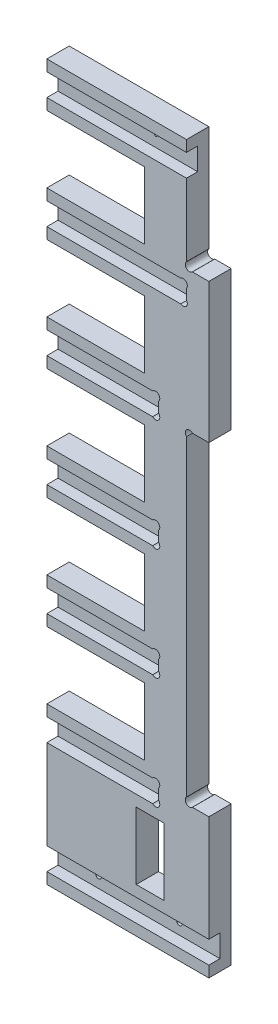
SolidWorks part; units mm, degrees
ref_plane "Plan de face" through (0, 0, 0) normal (0, 0, 1) x (1, 0, 0)
ref_plane "Plan de dessus" through (0, 0, 0) normal (0, 1, 0) x (1, 0, 0)
ref_plane "Plan de droite" through (0, 0, 0) normal (1, 0, 0) x (0, 0, -1)
sketch "Esquisse1" plane through (0, 0, 0) normal (0, 0, 1) x (1, 0, 0)
  line L0 (-47.2113, 8.0146) -> (30.577, 8.0146) construction
  line L1 (30.577, 186.1359) -> (30.577, 224.0146)
  line L2 (-19.423, 144.0146) -> (-19.423, 128.0146)
  line L3 (-19.423, -31.9854) -> (30.577, -31.9854)
  line L4 (30.577, 131.8932) -> (30.577, 20.1359)
  line L5 (-47.2113, 48.0146) -> (30.577, 48.0146) construction
  line L6 (-47.2113, 88.0146) -> (30.577, 88.0146) construction
  line L7 (-47.2113, 128.0146) -> (30.577, 128.0146) construction
  line L8 (-47.2113, 168.0146) -> (30.577, 168.0146) construction
  line L9 (22.577, 168.0146) -> (22.577, -39.7784) construction
  line L10 (-25.8665, 24.0146) -> (35.1678, 24.0146) construction
  line L11 (-22.7631, 64.0146) -> (35.1678, 64.0146) construction
  line L12 (-22.7631, 104.0146) -> (35.1678, 104.0146) construction
  line L13 (-22.7631, 144.0146) -> (38.577, 144.0146) construction
  line L14 (5.577, 173.4418) -> (5.577, -34.7699) construction
  line L15 (15.577, 173.4418) -> (15.577, -34.7699) construction
  line L16 (-19.423, 144.0146) -> (15.577, 144.0146)
  line L17 (-19.423, 128.0146) -> (15.577, 128.0146)
  line L18 (-19.423, 64.0146) -> (-19.423, 48.0146)
  line L19 (-19.423, 104.0146) -> (15.577, 104.0146)
  line L20 (15.577, 128.0146) -> (15.577, 104.0146)
  line L21 (-19.423, 88.0146) -> (15.577, 88.0146)
  line L22 (-19.423, 24.0146) -> (-19.423, -31.9854)
  line L23 (-19.423, 64.0146) -> (15.577, 64.0146)
  line L24 (15.577, 88.0146) -> (15.577, 64.0146)
  line L25 (-19.423, 48.0146) -> (15.577, 48.0146)
  line L26 (30.577, 224.0146) -> (-19.423, 224.0146)
  line L27 (-19.423, 24.0146) -> (15.577, 24.0146)
  line L28 (15.577, 48.0146) -> (15.577, 24.0146)
  line L29 (12.577, 8.0146) -> (22.577, 8.0146)
  line L30 (12.577, 8.0146) -> (12.577, -15.9854)
  line L31 (12.577, -15.9854) -> (22.577, -15.9854)
  line L32 (22.577, 8.0146) -> (22.577, -15.9854)
  line L33 (15.577, 144.0146) -> (15.577, 168.0146)
  line L34 (-19.423, 104.0146) -> (-19.423, 88.0146)
  line L35 (-19.423, 168.0146) -> (15.577, 168.0146)
  line L36 (-19.423, 168.0146) -> (-19.423, 184.0146)
  line L37 (-19.423, 184.0146) -> (15.577, 184.0146)
  line L39 (-19.423, 224.0146) -> (-19.423, 208.0319)
  line L40 (-19.423, 208.0319) -> (15.577, 208.0319)
  line L41 (15.577, 208.0319) -> (15.577, 184.0146)
  line L42 (-19.423, -29.9854) -> (30.577, -29.9854) construction
  line L43 (30.577, -31.9854) -> (38.577, -31.9854)
  line L44 (38.577, -31.9854) -> (38.577, 18.0146)
  line L45 (38.577, 18.0146) -> (32.6983, 18.0146)
  line L47 (32.6983, 184.0146) -> (38.577, 184.0146)
  line L48 (38.577, 184.0146) -> (38.577, 134.0146)
  line L49 (38.577, 134.0146) -> (32.6983, 134.0146)
  arc A2 (30.577, 20.1359) -> (32.6983, 18.0146) centre (31.6377, 19.0752) ccw
  arc A3 (30.577, 186.1359) -> (32.6983, 184.0146) centre (31.6377, 185.0752) ccw
  arc A4 (32.6983, 134.0146) -> (30.577, 131.8932) centre (31.6377, 132.9539) ccw
  dimension "D1" = 40
  dimension "D2" = 40
  dimension "D3" = 40
  dimension "D4" = 40
  dimension "D5" = 40
  dimension "D6" = 8
  dimension "D7" = 16
  dimension "D8" = 16
  dimension "D9" = 16
  dimension "D10" = 16
  dimension "D11" = 50
  dimension "D12" = 10
  dimension "D13" = 16
  dimension "D14" = 256
  dimension "D15" = 4
extrude "Boss.-Extru.1" add sketch "Esquisse1" along normal blind 8
sketch "Esquisse2" plane through (0, 0, 8) normal (0, 0, 1) x (1, 0, 0)
  line L0 (-19.423, 144.0146) -> (-19.423, 128.0146) construction
  line L1 (-19.423, 140.0146) -> (18.4557, 140.0146)
  line L2 (-19.423, 140.0146) -> (-19.423, 132.0146)
  line L3 (-19.423, 132.0146) -> (18.4557, 132.0146)
  line L4 (20.577, 137.8932) -> (20.577, 134.1359)
  line L5 (15.577, 144.0146) -> (-19.423, 144.0146) construction
  line L6 (-19.423, 128.0146) -> (15.577, 128.0146) construction
  line L7 (-19.423, 104.0146) -> (-19.423, 88.0146) construction
  line L8 (-19.423, 100.0146) -> (18.4557, 100.0146)
  line L9 (-19.423, 100.0146) -> (-19.423, 92.0146)
  line L10 (-19.423, 92.0146) -> (18.4557, 92.0146)
  line L11 (20.577, 97.8932) -> (20.577, 94.1359)
  line L12 (-19.423, 64.0146) -> (-19.423, 48.0146) construction
  line L13 (-19.423, 60.0146) -> (18.4557, 60.0146)
  line L14 (-19.423, 60.0146) -> (-19.423, 52.0146)
  line L15 (-19.423, 52.0146) -> (18.4557, 52.0146)
  line L16 (20.577, 57.8932) -> (20.577, 54.1359)
  line L17 (15.577, 104.0146) -> (-19.423, 104.0146) construction
  line L18 (-19.423, 88.0146) -> (15.577, 88.0146) construction
  line L19 (15.577, 64.0146) -> (-19.423, 64.0146) construction
  line L20 (-19.423, 48.0146) -> (15.577, 48.0146) construction
  line L21 (-19.423, 184.0146) -> (-19.423, 168.0146) construction
  line L22 (-19.423, 180.0146) -> (28.5105, 180.0146)
  line L23 (-19.423, 180.0146) -> (-19.423, 172.0146)
  line L24 (-19.423, 172.0146) -> (28.5105, 172.0146)
  line L25 (30.577, 177.8932) -> (30.577, 174.1359)
  line L26 (-19.423, 168.0146) -> (15.577, 168.0146) construction
  line L27 (15.577, 184.0146) -> (-19.423, 184.0146) construction
  line L28 (-19.423, 24.0146) -> (-19.423, -31.9854) construction
  line L29 (-19.423, 20.0146) -> (18.4557, 20.0146)
  line L30 (-19.423, 20.0146) -> (-19.423, 12.0146)
  line L31 (-19.423, 12.0146) -> (18.4557, 12.0146)
  line L32 (20.577, 17.8932) -> (20.577, 14.1359)
  line L33 (-19.423, 24.0146) -> (15.577, 24.0146) construction
  line L34 (34.1433, 212.0319) -> (-19.423, 212.0319)
  line L35 (-19.423, 224.0146) -> (-19.423, 208.0319) construction
  line L36 (-19.423, 212.0319) -> (-19.423, 220.0146)
  line L37 (-19.423, 220.0146) -> (34.1433, 220.0146)
  line L38 (34.1433, 212.0319) -> (34.1433, 220.0146)
  line L39 (-19.423, 208.0319) -> (15.577, 208.0319) construction
  line L40 (30.577, 224.0146) -> (-19.423, 224.0146) construction
  line L41 (-19.423, -27.9854) -> (38.577, -27.9854)
  line L42 (-19.423, 24.0146) -> (-19.423, -31.9854) construction
  line L43 (38.577, -31.9854) -> (38.577, 18.0146) construction
  line L44 (38.577, -27.9854) -> (38.577, -19.9854)
  line L45 (38.577, -19.9854) -> (-19.423, -19.9854)
  line L46 (-19.423, -19.9854) -> (-19.423, -27.9854)
  line L47 (-19.423, -31.9854) -> (38.577, -31.9854) construction
  line L48 (30.577, 186.1359) -> (30.577, 224.0146) construction
  arc A0 (30.577, 177.8932) -> (28.5105, 180.0146) centre (29.3721, 178.7867) ccw
  arc A1 (28.5105, 172.0146) -> (30.577, 174.1359) centre (29.3721, 173.2424) ccw
  arc A2 (20.577, 137.8932) -> (18.4557, 140.0146) centre (19.5163, 138.9539) ccw
  arc A3 (18.4557, 132.0146) -> (20.577, 134.1359) centre (19.5163, 133.0752) ccw
  arc A4 (20.577, 97.8932) -> (18.4557, 100.0146) centre (19.5163, 98.9539) ccw
  arc A5 (18.4557, 92.0146) -> (20.577, 94.1359) centre (19.5163, 93.0752) ccw
  arc A6 (20.577, 57.8932) -> (18.4557, 60.0146) centre (19.5163, 58.9539) ccw
  arc A7 (18.4557, 52.0146) -> (20.577, 54.1359) centre (19.5163, 53.0752) ccw
  arc A8 (20.577, 17.8932) -> (18.4557, 20.0146) centre (19.5163, 18.9539) ccw
  arc A9 (18.4557, 12.0146) -> (20.577, 14.1359) centre (19.5163, 13.0752) ccw
  dimension "D10" = 4
  dimension "D14" = 1.5
  dimension "D15" = 1.5
  dimension "D1" = 4
  dimension "D2" = 4
  dimension "D3" = 4
  dimension "D4" = 4
  dimension "D5" = 4
  dimension "D6" = 4
  dimension "D7" = 4
  dimension "D8" = 4
  dimension "D9" = 4
  dimension "D11" = 4
  dimension "D12" = 4
  dimension "D13" = 0
extrude "Enlèv. mat.-Extru.1" cut sketch "Esquisse2" against normal blind 4
sketch "Esquisse3" plane through (0, 0, 4) normal (0, 0, 1) x (1, 0, 0)
  line L0 (30.577, 216.0233) -> (15.577, 216.0233) construction
  line L1 (30.577, 220.0146) -> (30.577, 212.0319) construction
  line L2 (-19.423, -23.9854) -> (38.577, -23.9854) construction
  line L3 (-19.423, -19.9854) -> (-19.423, -27.9854) construction
  line L4 (38.577, -27.9854) -> (38.577, -19.9854) construction
  line L5 (38.577, -23.9854) -> (38.577, -19.9854) construction
  line L6 (38.577, -19.9854) -> (9.577, -19.9854) construction
  line L7 (38.577, -19.9854) -> (-19.423, -19.9854) construction
  line L8 (9.577, -19.9854) -> (9.577, -23.9854) construction
  line L9 (24.077, -19.9854) -> (24.077, -23.9854) construction
  circle A0 centre (15.577, 216.0233) radius 0.5
  circle A1 centre (24.077, -23.9854) radius 1
  circle A2 centre (-4.923, -23.9854) radius 1
extrude "Enlèv. mat.-Extru.2" cut sketch "Esquisse3" against normal blind 4
